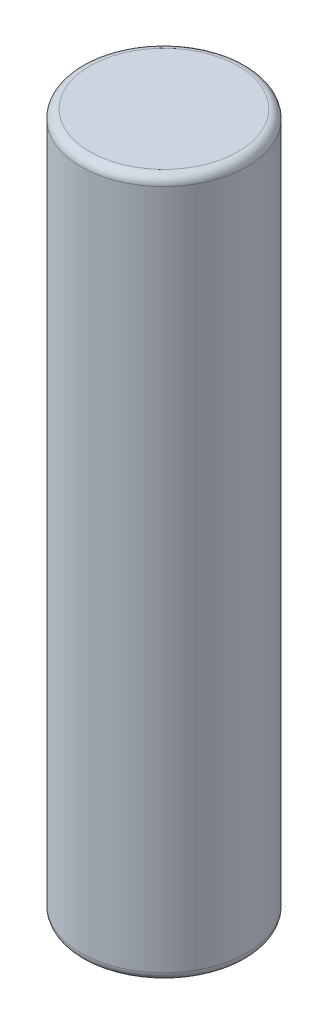
SolidWorks part; units mm, degrees
ref_plane "前视基准面" through (0, 0, 0) normal (0, 0, 1) x (1, 0, 0)
ref_plane "上视基准面" through (0, 0, 0) normal (0, 1, 0) x (1, 0, 0)
ref_plane "右视基准面" through (0, 0, 0) normal (1, 0, 0) x (0, 0, -1)
other "Configuration Table"
sketch "草图1" plane through (0, 0, 0) normal (0, 1, 0) x (1, 0, 0)
  circle A0 centre (0, 0) radius 9.5
  dimension "D1" = 19
extrude "凸台-拉伸1" add sketch "草图1" along normal blind 80
fillet "圆角1" radius 1 2 edges at (0, 0, 9.5) (0, 80, 9.5)
